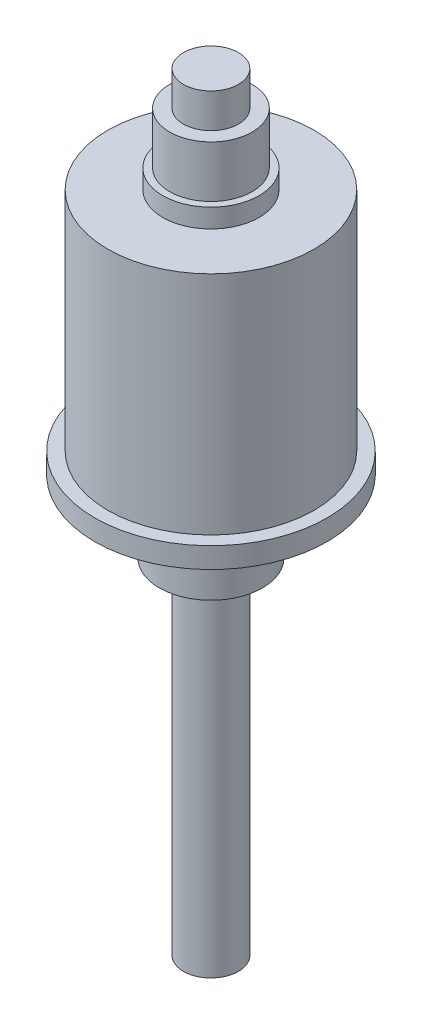
SolidWorks part; units mm, degrees
material "AISI 1035 Steel (SS)"
ref_plane "Front Plane" through (0, 0, 0) normal (0, 0, 1) x (1, 0, 0)
ref_plane "Top Plane" through (0, 0, 0) normal (0, 1, 0) x (1, 0, 0)
ref_plane "Right Plane" through (0, 0, 0) normal (1, 0, 0) x (0, 0, -1)
sketch "Sketch2" plane through (0, 0, 0) normal (0, 0, 1) x (1, 0, 0)
  line L0 (0, 40.0334) -> (0, -27.2464) construction
  line L11 (0, 0) -> (-4, 0)
  line L12 (-4, 0) -> (-4, -5)
  line L13 (-4, -5) -> (-6, -5)
  line L14 (-6, -5) -> (-6, -12.5)
  line L15 (-6, -12.5) -> (-7, -12.5)
  line L16 (-7, -12.5) -> (-7, -15.25)
  line L17 (-7, -15.25) -> (-14.9815, -15.25)
  line L18 (-14.9815, -15.25) -> (-14.9815, -48.11)
  line L26 (0, -111.61) -> (0, 0)
  line L28 (-16.8815, -51.11) -> (-16.8815, -48.11)
  line L29 (-16.8815, -48.11) -> (-14.9815, -48.11)
  line L30 (-16.8815, -51.11) -> (-9, -51.11)
  line L31 (-9, -51.11) -> (-9, -53.61)
  line L32 (-14.9815, -48.11) -> (-14.9815, -51.11) construction
  line L33 (-9, -53.61) -> (-7.5, -53.61)
  line L34 (-7.5, -53.61) -> (-7.5, -61.61)
  line L35 (-7.5, -61.61) -> (-4, -61.61)
  line L36 (-4, -61.61) -> (-4, -111.61)
  line L37 (-4, -111.61) -> (0, -111.61)
  dimension "D1" = 4
  dimension "D2" = 5
  dimension "D3" = 6
  dimension "D4" = 7.5
  dimension "D5" = 7
  dimension "D6" = 2.75
  dimension "D7" = 14.9815
  dimension "D8" = 32.86
  dimension "D10" = 3
  dimension "D11" = 9
  dimension "D12" = 2.5
  dimension "D13" = 7.5
  dimension "D14" = 8
  dimension "D15" = 4
  dimension "D16" = 50
  dimension "D9" = 1.9
revolve "Revolve1" add sketch "Sketch2" angle 360 about L0
equation "\"Stator_OD\"= 60'No Tolerance given"
equation "\"A\"=35.81 'taken off spec sheet for 06808 (A)"
equation "\"Rotor_ID\"= 30'No Tolerance Given"
equation "\"back_bearing_Thickness\"= 8'randomish, thinnest off mcmaster"
equation "\"back_bearing_OD\"= 25'currently non-sense"
equation "\"Stator_Gap\"= 0.0375'+- 0.0125 (From 1.3.3.1 Kollmorgen manual)"
equation "\"Back_mount_hole\"= 1.75'To be tapped to M2 (USE LOCKTITE)"
equation "\"facePlate_Mount_Hole\"= 5.75'To be tapped to M6"
equation "\"final_shaftD\"= 8'NEMA 23 shaft diameter. Should fit with harmonic?"
equation "\"back_bearing_ID\"= 15'Random number"
equation "\"rotor_shaftD\"= \"Rotor_ID\" - (\"rotor-shaft_gap\")*2'"
equation "\"back_bearing_IDOD\"= 18'Random number, OD of the inner bearing ring"
equation "\"final_shaftL\"= 50'random length. Idk"
equation "\"D1@Sketch2\" = \"final_shaftD\" / 2"
equation "\"D3@Sketch2\"=\"front_bearing_ID\"/2"
equation "\"D4@Sketch2\" = \"front_bearing_Thickness\" + 2.5"
equation "\"D5@Sketch2\"=\"front_bearing_IDOD\" / 2"
equation "\"D8@Sketch2\"=\"rotor_height\""
equation "\"front_bearing_ID\"= 12'random"
equation "\"front_bearing_OD\"= 20'random"
equation "\"front_bearing_IDOD\"= 14'random"
equation "\"front_bearing_Thickness\"= 5'randomish, thinnest off mcmaster"
equation "\"rotor_thickness\"= 2.4'measured off CAD"
equation "\"rotor_height\"= 32.86'+-0.075 taken off spec sheet for 06826 (C)"
equation "\"D11@Sketch2\"=\"back_bearing_IDOD\"/2"
equation "\"D13@Sketch2\"=\"back_bearing_ID\"/2"
equation "\"D14@Sketch2\"=\"back_bearing_Thickness\""
equation "\"D15@Sketch2\"=\"final_shaftD\"/2"
equation "\"D16@Sketch2\"=\"final_shaftL\""
equation "\"D9@Sketch2\"=\"rotor_thickness\"-0.5"
equation "\"rotor-shaft_gap\" = 0.0185 '+-0.0065 (from manual)"
equation "\"D7@Sketch2\"=\"Rotor_ID\"/2-\"rotor-shaft_gap\""
